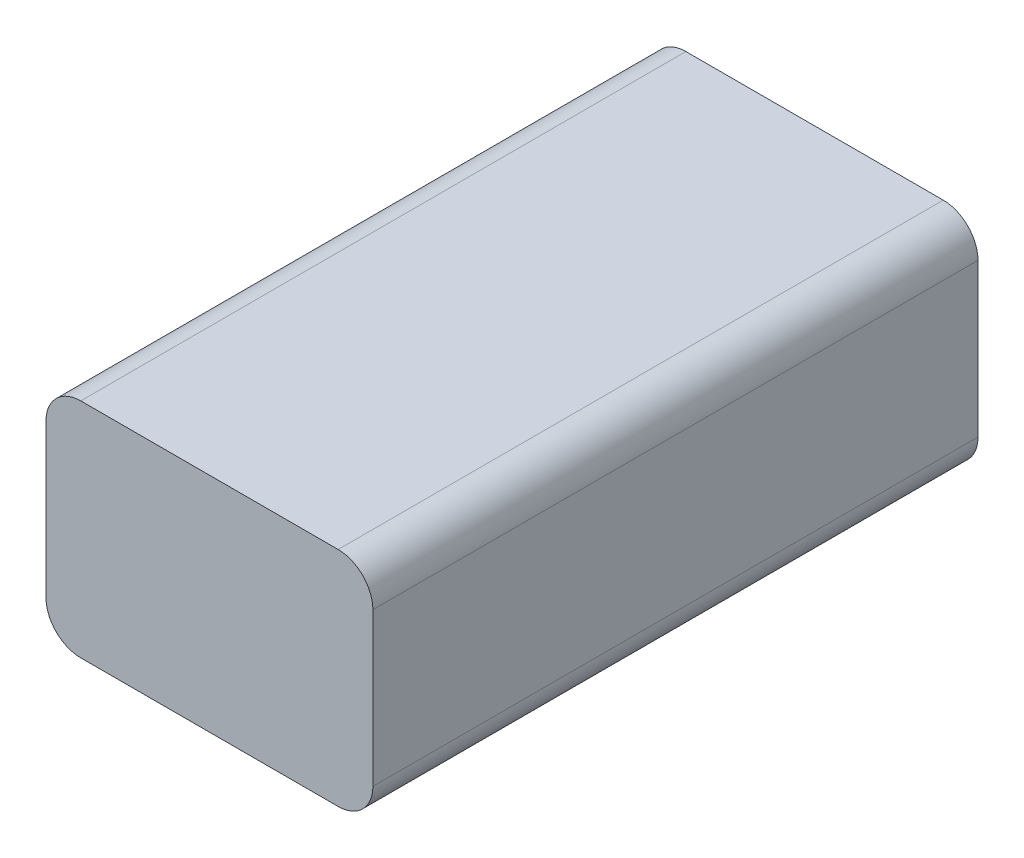
SolidWorks part; units mm, degrees
ref_plane "Front Plane" through (0, 0, 0) normal (0, 0, 1) x (1, 0, 0)
ref_plane "Top Plane" through (0, 0, 0) normal (0, 1, 0) x (1, 0, 0)
ref_plane "Right Plane" through (0, 0, 0) normal (1, 0, 0) x (0, 0, -1)
sketch "Sketch1" plane through (0, 0, 0) normal (0, 0, 1) x (1, 0, 0)
  line L1 (23.5, 16) -> (-23.5, 16)
  line L2 (23.5, 16) -> (23.5, -16)
  line L3 (23.5, -16) -> (-23.5, -16)
  line L4 (-23.5, 16) -> (-23.5, -16)
  line L5 (23.5, 16) -> (-23.5, -16) construction
  line L6 (23.5, -16) -> (-23.5, 16) construction
  point P0 (0, 0)
  dimension "D1" = 47
  dimension "D2" = 32
extrude "Boss-Extrude1" add sketch "Sketch1" along normal blind 87
fillet "Fillet1" radius 5 4 edges at (-23.5, -16, 43.5) (-23.5, 16, 43.5) (23.5, -16, 43.5) (23.5, 16, 43.5)
